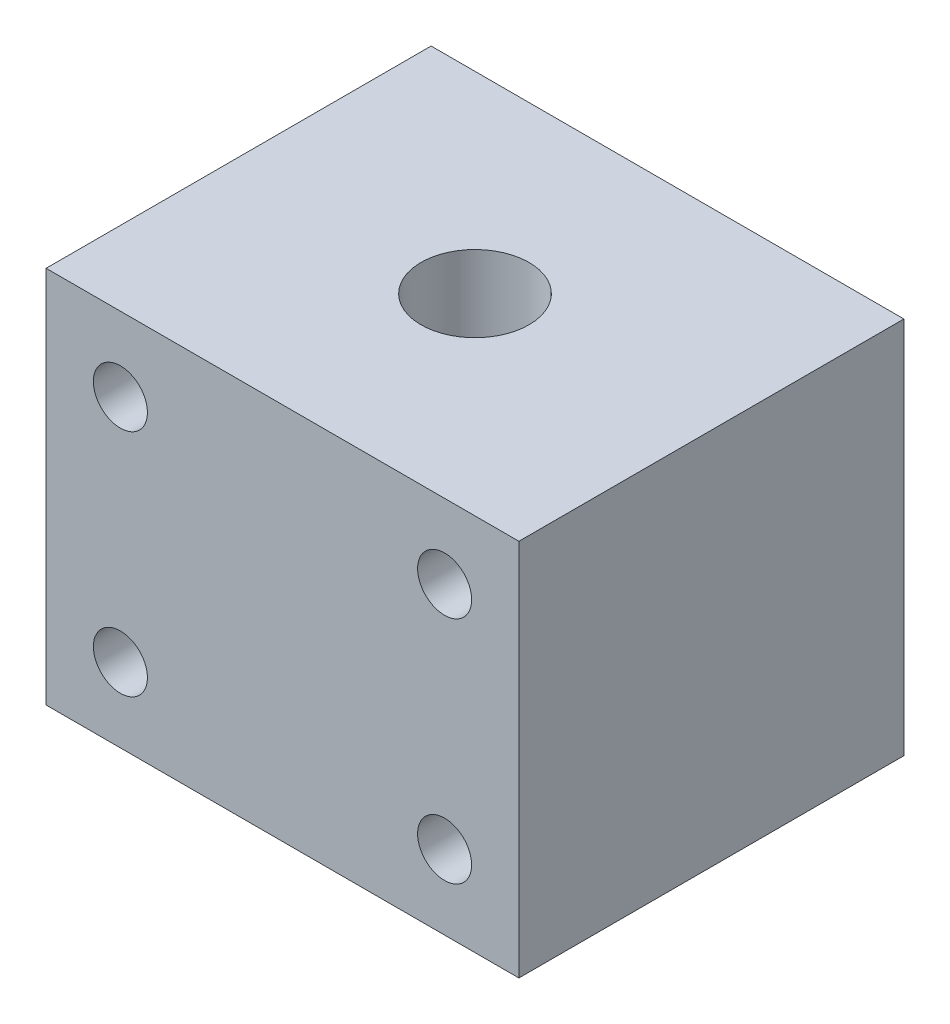
SolidWorks part; units mm, degrees
ref_plane "Front Plane" through (0, 0, 0) normal (0, 0, 1) x (1, 0, 0)
ref_plane "Top Plane" through (0, 0, 0) normal (0, 1, 0) x (1, 0, 0)
ref_plane "Right Plane" through (0, 0, 0) normal (1, 0, 0) x (0, 0, -1)
sketch "Sketch1" plane through (0, 0, 0) normal (0, 0, 1) x (1, 0, 0)
  line L0 (17.5, 28) -> (17.5, 0) construction
  line L1 (0, 0) -> (35, 0)
  line L2 (0, 0) -> (0, 28)
  line L3 (0, 28) -> (35, 28)
  line L4 (35, 0) -> (35, 28)
  line L5 (0, 14) -> (35, 14) construction
  line L6 (5.5, 22.5) -> (5.5, 5.5) construction
  line L7 (29.5, 22.5) -> (29.5, 5.5) construction
  circle A1 centre (5.5, 22.5) radius 2
  circle A2 centre (29.5, 22.5) radius 2
  circle A3 centre (5.5, 5.5) radius 2
  circle A4 centre (29.5, 5.5) radius 2
  point P17 (0, 0)
  point P18 (0, 0)
  point P19 (2.5481, 5.4659)
  point P20 (5.9882, 5.5805)
  dimension "D8" = 4
  dimension "D9" = 4
  dimension "D10" = 4
  dimension "D11" = 4
  dimension "D1" = 28
  dimension "D2" = 35
  dimension "D3" = 24
  dimension "D4" = 24
  dimension "D5" = 17
  dimension "D6" = 8.5
  dimension "D7" = 12
extrude "Boss-Extrude1" add sketch "Sketch1" along normal blind 28.5
sketch "Sketch2" plane through (0, 0, 0) normal (0, -1, 0) x (1, 0, 0)
  line L0 (17.5, 28.5) -> (17.5, 0) construction
  line L1 (0, 28.5) -> (35, 28.5) construction
  line L2 (0, 0) -> (35, 0) construction
  line L3 (0, 14.25) -> (35, 14.25) construction
  line L4 (0, 28.5) -> (0, 0) construction
  line L5 (35, 28.5) -> (35, 0) construction
  circle A0 centre (17.5, 14.25) radius 4
  dimension "D1" = 8
extrude "Cut-Extrude1" cut sketch "Sketch2" against normal through all
